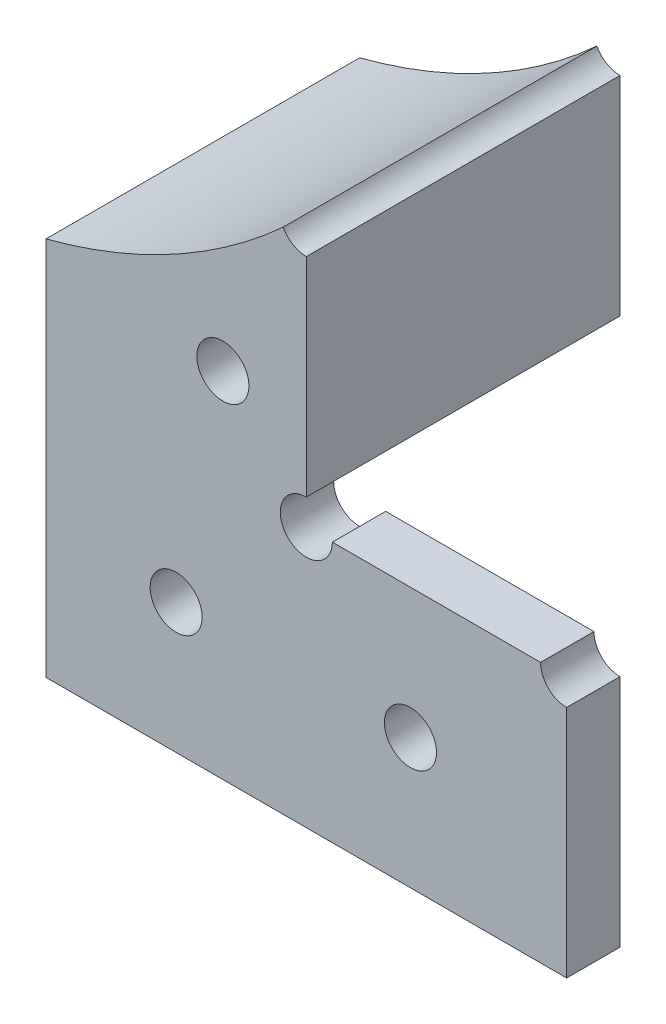
SolidWorks part; units mm, degrees
ref_plane "前视基准面" through (0, 0, 0) normal (0, 0, 1) x (1, 0, 0)
ref_plane "上视基准面" through (0, 0, 0) normal (0, 1, 0) x (1, 0, 0)
ref_plane "右视基准面" through (0, 0, 0) normal (1, 0, 0) x (0, 0, -1)
sketch "草图1" plane through (0, 0, 0) normal (0, 0, 1) x (1, 0, 0)
  line L1 (-10, -10) -> (10, -10)
  line L2 (-10, -10) -> (-10, 10)
  line L3 (-10, 10) -> (10, 10)
  line L4 (10, -10) -> (10, 10)
  line L5 (-10, -10) -> (10, 10) construction
  line L6 (-10, 10) -> (10, -10) construction
  circle A0 centre (0, 0) radius 2
  point P0 (0, 0)
  dimension "D3" = 4
  dimension "D1" = 20
  dimension "D2" = 20
extrude "凸台-拉伸1" add sketch "草图1" along normal blind 4.1
sketch "草图2" plane through (0, 0, 4.1) normal (0, 0, 1) x (1, 0, 0)
  line L0 (10, -10) -> (10, 10) construction
  line L1 (-10, 10) -> (10, 10)
  line L2 (-10, 10) -> (-10, 30)
  line L3 (-10, 30) -> (10, 30)
  line L4 (10, 10) -> (10, 30)
  dimension "D1" = 20
extrude "凸台-拉伸2" add sketch "草图2" against normal blind 24.1
sketch "草图3" plane through (0, 0, 4.1) normal (0, 0, 1) x (1, 0, 0)
  line L2 (0, -10) -> (0, 30) construction
  line L9 (-10, -10) -> (10, -10) construction
  line L11 (-10, 30) -> (9.206, 30)
  line L12 (-10, 19.1784) -> (-10, 30)
  arc A0 (9.206, 30) -> (-10, 19.1784) centre (-20.8, 60.8) cw
  point P0 (20.8, 60.8)
  point P11 (57.1396, 71.9101)
extrude "切除-拉伸1" cut sketch "草图3" against normal through all
sketch "草图4" plane through (0, 0, 4.1) normal (0, 0, 1) x (1, 0, 0)
  line L0 (-10, -10) -> (10, 30) construction
  line L2 (10, -10) -> (10, 30) construction
  line L3 (-10, 19.1784) -> (10, 19.1784) construction
  circle A1 centre (3.5892, 17.1784) radius 2
  dimension "D1" = 4
extrude "切除-拉伸2" cut sketch "草图4" against normal through all
sketch "草图5" plane through (10, 0, 0) normal (1, 0, 0) x (0, 0, -1)
  line L0 (-4.1, -10) -> (-4.1, 30) construction
  line L1 (0, -10) -> (-4.1, -10)
  line L2 (0, -10) -> (0, 10)
  line L3 (0, 10) -> (-4.1, 10)
  line L4 (-4.1, -10) -> (-4.1, 10)
extrude "凸台-拉伸3" add sketch "草图5" along normal blind 20
sketch "草图7" plane through (0, 0, 4.1) normal (0, 0, 1) x (1, 0, 0)
  line L0 (10, 10) -> (10, 30) construction
  circle A0 centre (10, 10) radius 2
  circle A1 centre (10, 30) radius 2
  circle A2 centre (30, 10) radius 2
  circle A3 centre (18, 0) radius 2
  dimension "D1" = 4
  dimension "D2" = 4
  dimension "D3" = 4
  dimension "D4" = 4
  dimension "D5" = 8
extrude "切除-拉伸3" cut sketch "草图7" against normal through all
